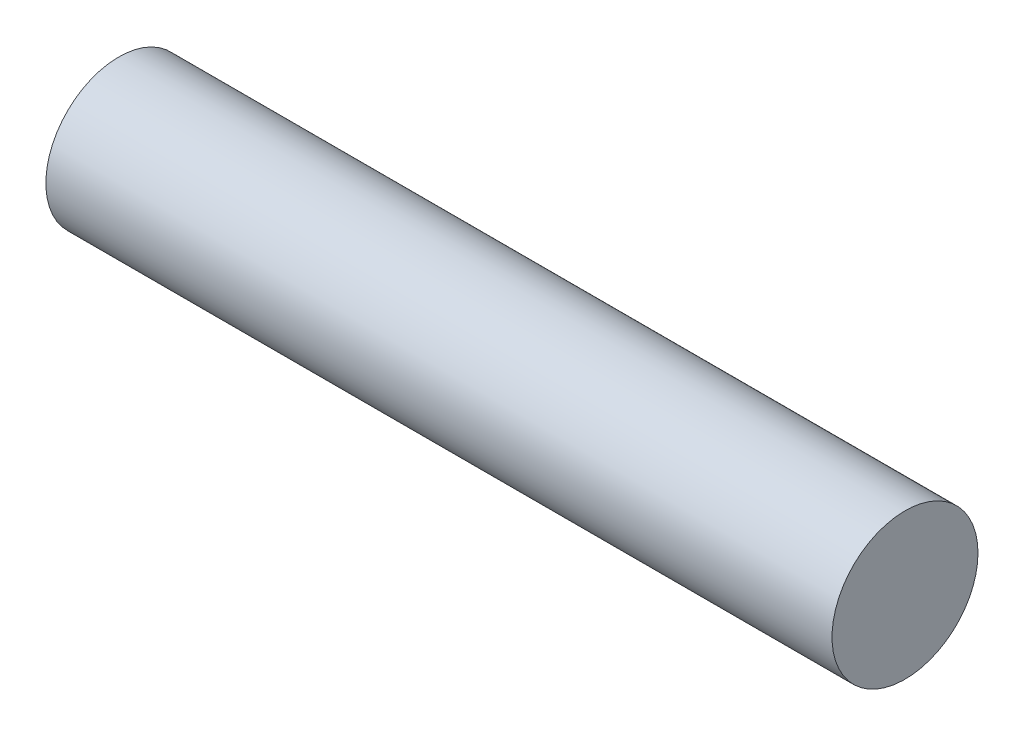
SolidWorks part; units mm, degrees
ref_plane "Plan de face" through (0, 0, 0) normal (0, 0, 1) x (1, 0, 0)
ref_plane "Plan de dessus" through (0, 0, 0) normal (0, 1, 0) x (1, 0, 0)
ref_plane "Plan de droite" through (0, 0, 0) normal (1, 0, 0) x (0, 0, -1)
sketch "Sketch1" plane through (0, 0, 0) normal (1, 0, 0) x (0, 0, -1)
  circle A0 centre (0, 0) radius 44.27
  dimension "D1" = 88.54
extrude "Boss-Extrude1" add sketch "Sketch1" along normal blind 476.85
equation "\"D1@Sketch1\"=2*44.27"
